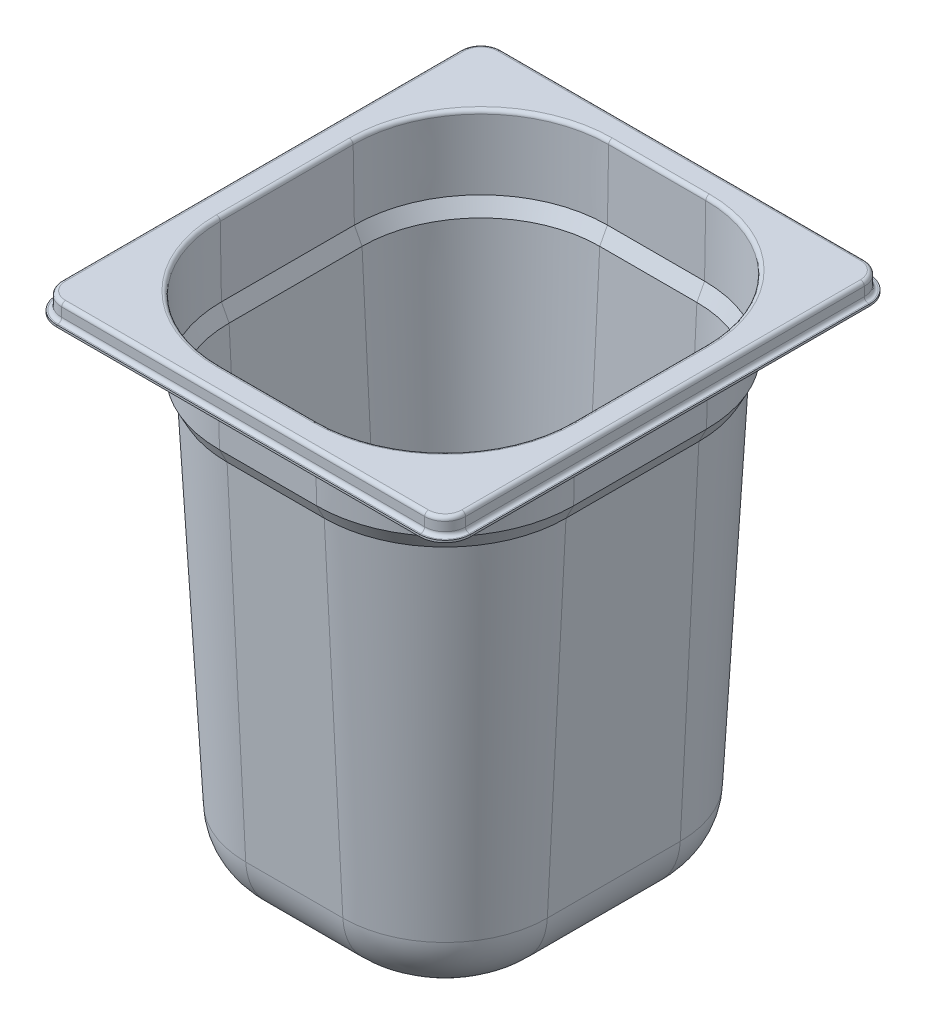
SolidWorks part; units mm, degrees
ref_plane "Front Plane" through (0, 0, 0) normal (0, 0, 1) x (1, 0, 0)
ref_plane "Top Plane" through (0, 0, 0) normal (0, 1, 0) x (1, 0, 0)
ref_plane "Right Plane" through (0, 0, 0) normal (1, 0, 0) x (0, 0, -1)
sketch "Sketch1" plane through (0, 0, 0) normal (0, 1, 0) x (1, 0, 0)
  line L1 (10, 0) -> (152, 0)
  line L2 (0, 10) -> (0, 166)
  line L3 (10, 176) -> (152, 176)
  line L4 (162, 10) -> (162, 166)
  arc A0 (152, 0) -> (162, 10) centre (152, 10) ccw
  arc A1 (10, 0) -> (0, 10) centre (10, 10) cw
  arc A2 (152, 176) -> (162, 166) centre (152, 166) cw
  arc A3 (0, 166) -> (10, 176) centre (10, 166) cw
  point P7 (162, 0)
  point P10 (0, 0)
  point P15 (0, 176)
  dimension "D3" = 10
  dimension "D1" = 162
  dimension "D2" = 176
ref_plane "Plane1" through (0, 0, -10) normal (0, 0, 1) x (1, 0, 0)
sketch "Sketch2" plane through (0, 0, -10) normal (0, 0, 1) x (1, 0, 0)
  line L0 (0, -6.5) -> (0.5, -6.5)
  line L1 (2, -5) -> (2, -1.5)
  line L2 (10, 0) -> (0, 0) construction
  line L3 (3.5, 0) -> (10.5278, 0)
  line L4 (12.0276, -1.4738) -> (12.4993, -28.5)
  line L5 (12.4993, -28.5) -> (15.4993, -34.2)
  line L6 (15.4993, -34.2) -> (22.8001, -173.5084)
  line L7 (47.7659, -197.2) -> (57.7659, -197.2)
  line L9 (10, 0) -> (152, 0) construction
  line L10 (0, -7.3) -> (0.5, -7.3)
  line L11 (2.8, -5) -> (2.8, -1.5)
  line L12 (3.5, -0.8) -> (10.5278, -0.8)
  line L13 (11.2277, -1.4878) -> (11.7027, -28.7042)
  line L14 (11.7027, -28.7042) -> (14.7096, -34.4172)
  line L15 (14.7096, -34.4172) -> (22.0012, -173.5503)
  line L16 (47.7659, -198) -> (57.7659, -198)
  line L17 (0, -6.5) -> (0, -7.3)
  line L18 (57.7659, -197.2) -> (57.7659, -198)
  arc A0 (22.8001, -173.5084) -> (47.7659, -197.2) centre (47.7659, -172.2) ccw
  arc A1 (10.5278, 0) -> (12.0276, -1.4738) centre (10.5278, -1.5) cw
  arc A2 (0.5, -6.5) -> (2, -5) centre (0.5, -5) ccw
  arc A3 (2, -1.5) -> (3.5, 0) centre (3.5, -1.5) cw
  arc A4 (0.5, -7.3) -> (2.8, -5) centre (0.5, -5) ccw
  arc A5 (2.8, -1.5) -> (3.5, -0.8) centre (3.5, -1.5) cw
  arc A6 (10.5278, -0.8) -> (11.2277, -1.4878) centre (10.5278, -1.5) cw
  arc A7 (22.0012, -173.5503) -> (47.7659, -198) centre (47.7659, -172.2) ccw
  point P24 (12.0018, 0)
  point P29 (2, 0)
  dimension "D1" = 25
  dimension "D12" = 1.5
  dimension "D2" = 10
  dimension "D3" = 6.5
  dimension "D4" = 12
  dimension "D5" = 2
  dimension "D6" = 93
  dimension "D7" = 91
  dimension "D8" = 28.5
  dimension "D9" = 34.2
  dimension "D10" = 3
  dimension "D11" = 197.2
  dimension "D13" = 0.8
sketch "Sketch7" plane through (0, 0, -10) normal (0, 0, 1) x (1, 0, 0)
  line L0 (2, -5) -> (2, -1.5) construction
  line L1 (0, -6.5) -> (0.5, -6.5) construction
  line L2 (0, -6.5) -> (0, -7.3) construction
  line L3 (0, -7.3) -> (0.5, -7.3) construction
  line L4 (2.8, -5) -> (2.8, -1.5) construction
  line L5 (2, -5) -> (2, -1.5)
  line L6 (0, -6.5) -> (0.5, -6.5)
  line L7 (0, -6.5) -> (0, -7.3)
  line L8 (0, -7.3) -> (0.5, -7.3)
  line L9 (2.8, -5) -> (2.8, -1.5)
  line L10 (3.5, 0) -> (3.5, -0.8)
  arc A0 (3.5, -0.8) -> (2.8, -1.5) centre (3.5, -1.5) ccw construction
  arc A1 (3.5, 0) -> (2, -1.5) centre (3.5, -1.5) ccw construction
  arc A2 (0.5, -6.5) -> (2, -5) centre (0.5, -5) ccw construction
  arc A3 (0.5, -7.3) -> (2.8, -5) centre (0.5, -5) ccw construction
  arc A4 (3.5, -0.8) -> (2.8, -1.5) centre (3.5, -1.5) ccw
  arc A5 (3.5, 0) -> (2, -1.5) centre (3.5, -1.5) ccw
  arc A6 (0.5, -6.5) -> (2, -5) centre (0.5, -5) ccw
  arc A7 (0.5, -7.3) -> (2.8, -5) centre (0.5, -5) ccw
sweep "Sweep9" add profiles "Sketch7" path "Sketch1"
sketch "Sketch9" plane through (0, 0, 0) normal (0, 1, 0) x (1, 0, 0)
  line L0 (62, 164) -> (100, 164)
  line L1 (150, 114) -> (150, 62)
  line L2 (100, 12) -> (62, 12)
  line L3 (12, 62) -> (12, 114)
  line L4 (26.6447, 26.6447) -> (5.4038, 5.4038) construction
  line L5 (135.3553, 149.3553) -> (156.5962, 170.5962) construction
  line L6 (135.3553, 26.6447) -> (156.5962, 5.4038) construction
  arc A0 (100, 164) -> (150, 114) centre (100, 114) cw
  arc A1 (150, 62) -> (100, 12) centre (100, 62) cw
  arc A2 (62, 12) -> (12, 62) centre (62, 62) cw
  arc A3 (12, 114) -> (62, 164) centre (62, 114) cw
  arc A4 (3.5, 10) -> (10, 3.5) centre (10, 10) ccw construction
  arc A5 (158.5, 166) -> (152, 172.5) centre (152, 166) ccw construction
  arc A6 (152, 3.5) -> (158.5, 10) centre (152, 10) ccw construction
  dimension "D1" = 50
  dimension "D2" = 138
  dimension "D3" = 152
ref_plane "Plane2" through (0, 0, -62) normal (0, 0, 1) x (1, 0, 0)
sketch "Sketch10" plane through (0, 0, -62) normal (0, 0, 1) x (1, 0, 0)
  line L0 (10.5278, 0) -> (10.5278, -0.8)
  line L16 (2.8, -5) -> (2.8, -1.5)
  line L17 (3.5, -0.8) -> (10.5278, -0.8)
  line L18 (11.2277, -1.4878) -> (11.7027, -28.7042)
  line L19 (11.7027, -28.7042) -> (14.7096, -34.4172)
  line L20 (14.7096, -34.4172) -> (22.0012, -173.5503)
  line L21 (47.7659, -198) -> (57.7659, -198)
  line L22 (57.7659, -198) -> (57.7659, -197.2)
  line L23 (57.7659, -197.2) -> (47.7659, -197.2)
  line L24 (22.8001, -173.5084) -> (15.4993, -34.2)
  line L25 (15.4993, -34.2) -> (12.4993, -28.5)
  line L26 (12.4993, -28.5) -> (12.0276, -1.4738)
  line L27 (10.5278, 0) -> (3.5, 0)
  line L28 (2, -1.5) -> (2, -5)
  line L29 (0.5, -6.5) -> (0, -6.5)
  line L30 (0, -6.5) -> (0, -7.3)
  line L31 (0, -7.3) -> (0.5, -7.3)
  line L34 (11.2277, -1.4878) -> (11.7027, -28.7042)
  line L35 (11.7027, -28.7042) -> (14.7096, -34.4172)
  line L36 (14.7096, -34.4172) -> (22.0012, -173.5503)
  line L37 (47.7659, -198) -> (57.7659, -198)
  line L38 (57.7659, -198) -> (57.7659, -197.2)
  line L39 (57.7659, -197.2) -> (47.7659, -197.2)
  line L40 (22.8001, -173.5084) -> (15.4993, -34.2)
  line L41 (15.4993, -34.2) -> (12.4993, -28.5)
  line L42 (12.4993, -28.5) -> (12.0276, -1.4738)
  arc A8 (3.5, -0.8) -> (2.8, -1.5) centre (3.5, -1.5) ccw
  arc A9 (11.2277, -1.4878) -> (10.5278, -0.8) centre (10.5278, -1.5) ccw
  arc A10 (22.0012, -173.5503) -> (47.7659, -198) centre (47.7659, -172.2) ccw
  arc A11 (22.8001, -173.5084) -> (47.7659, -197.2) centre (47.7659, -172.2) ccw
  arc A12 (12.0276, -1.4738) -> (10.5278, 0) centre (10.5278, -1.5) ccw
  arc A13 (3.5, 0) -> (2, -1.5) centre (3.5, -1.5) ccw
  arc A14 (0.5, -6.5) -> (2, -5) centre (0.5, -5) ccw
  arc A15 (0.5, -7.3) -> (2.8, -5) centre (0.5, -5) ccw
  arc A17 (11.2277, -1.4878) -> (10.5278, -0.8) centre (10.5278, -1.5) ccw
  arc A18 (22.0012, -173.5503) -> (47.7659, -198) centre (47.7659, -172.2) ccw
  arc A19 (22.8001, -173.5084) -> (47.7659, -197.2) centre (47.7659, -172.2) ccw
  arc A20 (12.0276, -1.4738) -> (10.5278, 0) centre (10.5278, -1.5) ccw
  dimension "D1" = 0
sweep "Sweep10" add profiles "Sketch10" path "Sketch9"
sketch "Sketch11" plane through (0, 0, 0) normal (0, 1, 0) x (1, 0, 0)
  line L0 (158.5, 166) -> (158.5, 10) construction
  line L1 (152, 3.5) -> (10, 3.5) construction
  line L2 (3.5, 10) -> (3.5, 166) construction
  line L3 (10, 172.5) -> (152, 172.5) construction
  line L4 (158.5, 166) -> (158.5, 10)
  line L5 (152, 3.5) -> (10, 3.5)
  line L6 (3.5, 10) -> (3.5, 166)
  line L7 (10, 172.5) -> (152, 172.5)
  line L8 (62, 165.4722) -> (100, 165.4722) construction
  line L9 (151.4722, 114) -> (151.4722, 62) construction
  line L10 (10.5278, 62) -> (10.5278, 114) construction
  line L11 (10.5278, 62) -> (10.5278, 114)
  line L12 (151.4722, 114) -> (151.4722, 62)
  line L13 (62, 165.4722) -> (100, 165.4722)
  line L14 (100, 10.5278) -> (62, 10.5278) construction
  line L15 (100, 10.5278) -> (62, 10.5278)
  arc A0 (158.5, 166) -> (152, 172.5) centre (152, 166) ccw construction
  arc A1 (152, 3.5) -> (158.5, 10) centre (152, 10) ccw construction
  arc A2 (3.5, 10) -> (10, 3.5) centre (10, 10) ccw construction
  arc A3 (10, 172.5) -> (3.5, 166) centre (10, 166) ccw construction
  arc A4 (158.5, 166) -> (152, 172.5) centre (152, 166) ccw
  arc A5 (152, 3.5) -> (158.5, 10) centre (152, 10) ccw
  arc A6 (3.5, 10) -> (10, 3.5) centre (10, 10) ccw
  arc A7 (10, 172.5) -> (3.5, 166) centre (10, 166) ccw
  arc A8 (62, 165.4722) -> (10.5278, 114) centre (62, 114) ccw construction
  arc A9 (151.4722, 114) -> (100, 165.4722) centre (100, 114) ccw construction
  arc A10 (10.5278, 62) -> (62, 10.5278) centre (62, 62) ccw construction
  arc A11 (100, 10.5278) -> (151.4722, 62) centre (100, 62) ccw construction
  arc A12 (10.5278, 62) -> (62, 10.5278) centre (62, 62) ccw
  arc A13 (100, 10.5278) -> (151.4722, 62) centre (100, 62) ccw
  arc A14 (151.4722, 114) -> (100, 165.4722) centre (100, 114) ccw
  arc A15 (62, 165.4722) -> (10.5278, 114) centre (62, 114) ccw
extrude "Boss-Extrude2" add sketch "Sketch11" against normal blind 0.8
ref_plane "Plane3" through (0, -198, 0) normal (0, -1, 0) x (-1, 0, 0)
sketch "Sketch12" plane through (0, -198, 0) normal (0, -1, 0) x (-1, 0, 0)
  line L0 (-62, 118.2341) -> (-100, 118.2341) construction
  line L1 (-62, 118.2341) -> (-100, 118.2341)
  line L2 (-57.7659, 62) -> (-57.7659, 114) construction
  line L3 (-57.7659, 62) -> (-57.7659, 114)
  line L4 (-100, 57.7659) -> (-62, 57.7659) construction
  line L5 (-100, 57.7659) -> (-62, 57.7659)
  line L6 (-104.2341, 114) -> (-104.2341, 62) construction
  line L7 (-104.2341, 114) -> (-104.2341, 62)
  arc A0 (-100, 118.2341) -> (-104.2341, 114) centre (-100, 114) ccw construction
  arc A1 (-100, 118.2341) -> (-104.2341, 114) centre (-100, 114) ccw
  arc A2 (-57.7659, 114) -> (-62, 118.2341) centre (-62, 114) ccw construction
  arc A3 (-57.7659, 114) -> (-62, 118.2341) centre (-62, 114) ccw
  arc A4 (-62, 57.7659) -> (-57.7659, 62) centre (-62, 62) ccw construction
  arc A5 (-62, 57.7659) -> (-57.7659, 62) centre (-62, 62) ccw
  arc A6 (-104.2341, 62) -> (-100, 57.7659) centre (-100, 62) ccw construction
  arc A7 (-104.2341, 62) -> (-100, 57.7659) centre (-100, 62) ccw
extrude "Boss-Extrude3" add sketch "Sketch12" against normal blind 0.8
